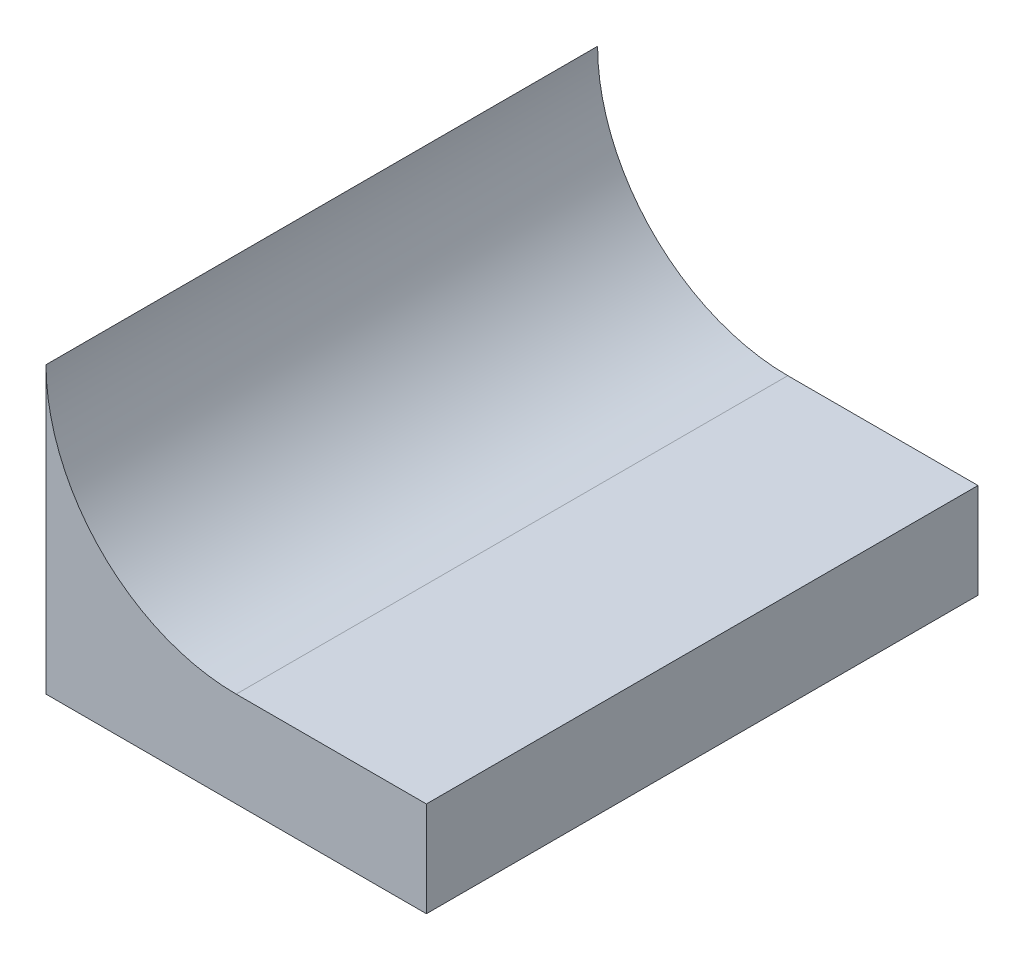
SolidWorks part; units mm, degrees
ref_plane "Front Plane" through (0, 0, 0) normal (0, 0, 1) x (1, 0, 0)
ref_plane "Top Plane" through (0, 0, 0) normal (0, 1, 0) x (1, 0, 0)
ref_plane "Right Plane" through (0, 0, 0) normal (1, 0, 0) x (0, 0, -1)
sketch "Sketch1" plane through (0, 0, 0) normal (0, 0, 1) x (1, 0, 0)
  line L0 (0, 0) -> (0.4, 0)
  line L1 (0.4, 0) -> (0.4, 0.1)
  line L2 (0.4, 0.1) -> (0.2, 0.1)
  line L3 (0, 0.1) -> (0, 0.3) construction
  line L5 (0, 0.3) -> (0.2, 0.3) construction
  line L6 (0, 0.3) -> (0, 0)
  arc A0 (0, 0.3) -> (0.2, 0.1) centre (0.2, 0.3) ccw
  dimension "D1" = 0.2
  dimension "D2" = 0.2
  dimension "D3" = 0.4
  dimension "D4" = 0.1
extrude "Boss-Extrude1" add sketch "Sketch1" along normal mid plane 0.58
